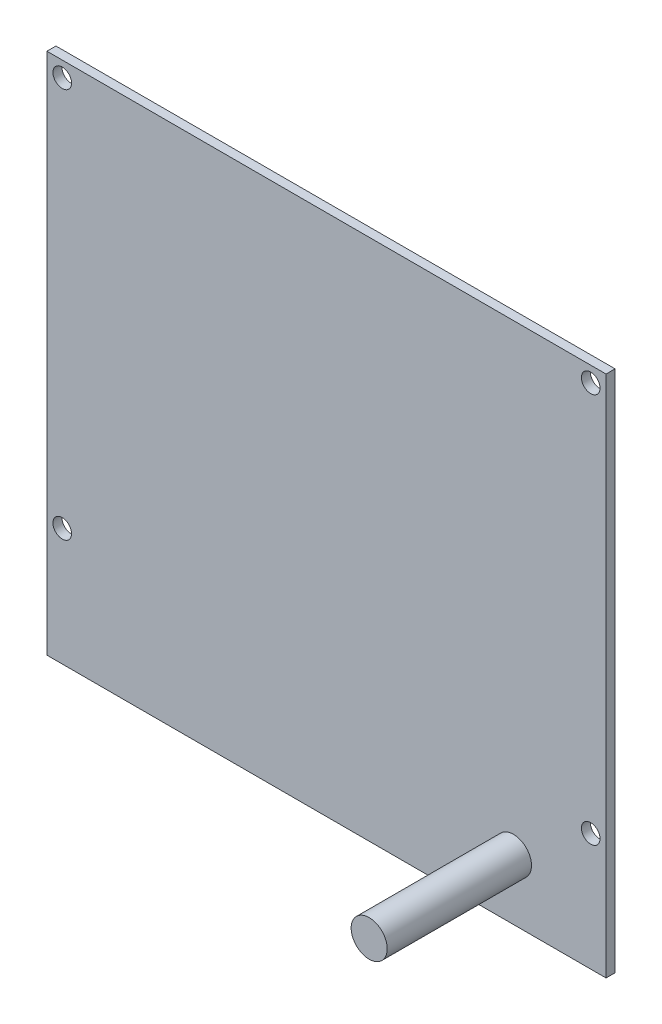
SolidWorks part; units mm, degrees
ref_plane "Alzado" through (0, 0, 0) normal (0, 0, 1) x (1, 0, 0)
ref_plane "Planta" through (0, 0, 0) normal (0, 1, 0) x (1, 0, 0)
ref_plane "Vista lateral" through (0, 0, 0) normal (1, 0, 0) x (0, 0, -1)
ref_plane "Plano1" through (0, 0, 0) normal (0, 0, -1) x (-1, 0, 0)
sketch "Croquis1" plane through (0, 0, 0) normal (0, 0, -1) x (-1, 0, 0)
  line L0 (46.5, -43.5) -> (46.5, 43.5)
  line L1 (46.5, 43.5) -> (-46.5, 43.5)
  line L2 (-46.5, 43.5) -> (-46.5, -43.5)
  line L3 (-46.5, -43.5) -> (46.5, -43.5)
extrude "Saliente-Extruir1" add sketch "Croquis1" against normal blind 1.5
ref_plane "Plano2" through (0, -33.5, 0) normal (0, 1, 0) x (1, 0, 0)
hole_wizard "Diámetro de taladro Ø3.1 (3.1)1" positions "Croquis8" profile "Croquis7" hole size "Ø3.1" standard "Ansi Metric"
sketch "Croquis8" plane through (0, 0, 0) normal (0, 0, -1) x (-1, 0, 0)
  point P0 (43.95, -23.95)
  point P1 (-43.95, -23.95)
  point P2 (43.95, 40.95)
  point P3 (-43.95, 40.95)
sketch "Croquis7" plane through (-43.95, -23.95, 0) normal (1, 0, 0) x (0, 1, 0)
  line L0 (0, 0) -> (0, 1.5)
  line L1 (0, 1.5) -> (1.55, 1.5)
  line L2 (1.55, 1.5) -> (1.55, 0)
  line L5 (1.55, 0) -> (0, 0)
  line L11 (0, -6.35) -> (0, 107.95) construction
  dimension "Diámetro de taladro hasta el siguiente" = 3.1
  dimension "Profundidad de taladro hasta el siguiente" = 1.5
sketch "Croquis9" plane through (0, 0, 1.5) normal (0, 0, 1) x (1, 0, 0)
  circle A0 centre (31.1, -33.5) radius 3
extrude "Saliente-Extruir4" add sketch "Croquis9" along normal blind 24
